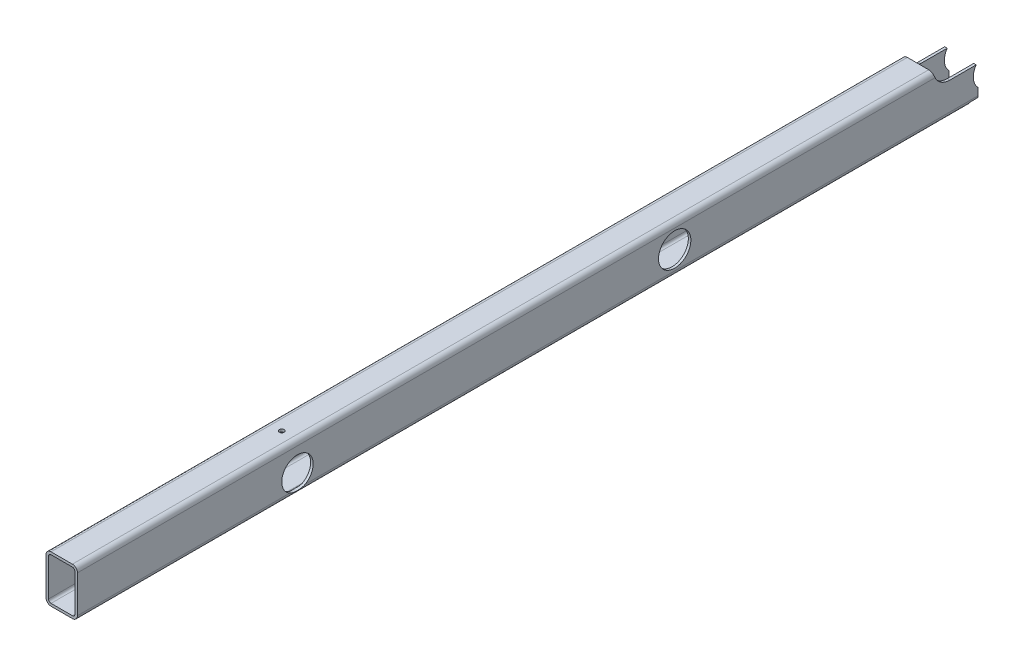
SolidWorks part; units mm, degrees
material "Q355"
ref_plane "前视基准面" through (0, 0, 0) normal (0, 0, 1) x (1, 0, 0)
ref_plane "上视基准面" through (0, 0, 0) normal (0, 1, 0) x (1, 0, 0)
ref_plane "右视基准面" through (0, 0, 0) normal (1, 0, 0) x (0, 0, -1)
sketch "草图1" plane through (0, 0, 0) normal (0, 0, 1) x (1, 0, 0)
  line L0 (16, -8) -> (84, -8)
  line L1 (16, 0) -> (84, 0)
  line L2 (0, -16) -> (0, -134)
  line L3 (16, -150) -> (84, -150)
  line L4 (100, -16) -> (100, -134)
  line L5 (92, -16) -> (92, -134)
  line L6 (16, -142) -> (84, -142)
  line L7 (8, -16) -> (8, -134)
  arc A0 (16, -150) -> (0, -134) centre (16, -134) cw
  arc A1 (84, -150) -> (100, -134) centre (84, -134) ccw
  arc A2 (100, -16) -> (84, 0) centre (84, -16) ccw
  arc A3 (0, -16) -> (16, 0) centre (16, -16) cw
  arc A4 (92, -16) -> (84, -8) centre (84, -16) ccw
  arc A5 (84, -142) -> (92, -134) centre (84, -134) ccw
  arc A6 (16, -142) -> (8, -134) centre (16, -134) cw
  arc A7 (8, -16) -> (16, -8) centre (16, -16) cw
  point P9 (100, -150)
  point P12 (100, 0)
  point P15 (0, 0)
  dimension "D3" = 16
  dimension "D1" = 150
  dimension "D2" = 100
  dimension "D4" = 8
extrude "凸台-拉伸1" add sketch "草图1" against normal blind 2865
sketch "草图2" plane through (0, 0, 0) normal (0, 1, 0) x (1, 0, 0)
  line L0 (100, 0) -> (30, 0)
  line L2 (30, 0) -> (30, 300)
  line L3 (30, 300) -> (100, 375)
  line L4 (100, 2865) -> (100, 0) construction
  line L5 (100, 375) -> (100, 0)
  line L6 (84, 0) -> (16, 0) construction
  dimension "D1" = 70
  dimension "D2" = 375
  dimension "D3" = 300
extrude "切除-拉伸1" [suppressed] cut sketch "草图2" against normal through all
sketch "草图4" plane through (100, 0, 0) normal (1, 0, 0) x (0, 0, -1)
  line L0 (2865, 0) -> (0, 0) construction
  line L1 (0, -16) -> (0, -134) construction
  circle A0 centre (2900, -75) radius 50
  dimension "D1" = 100
  dimension "D2" = 75
  dimension "D3" = 2900
extrude "切除-拉伸3" cut sketch "草图4" against normal through all
sketch "草图3" plane through (100, 0, 0) normal (1, 0, 0) x (0, 0, -1)
  line L0 (2775, -46) -> (2865, -46)
  line L1 (2865, 0) -> (0, 0) construction
  line L3 (2865, -134) -> (2865, -110.7071) construction
  line L4 (2865, -140) -> (2840, -140)
  line L5 (2865, 0) -> (2865, -46)
  line L6 (2840, -140) -> (2840, -150)
  line L7 (2865, -150) -> (0, -150) construction
  line L9 (2724.2457, 0) -> (2865, 0)
  line L10 (2865, -140) -> (2865, -150)
  line L11 (2865, -150) -> (2840, -150)
  line L13 (2900, -75) -> (2900, -154.9069) construction
  circle A1 centre (700, -90.5) radius 50
  arc A3 (2724.2457, 0) -> (2775, -46) centre (2775, 5) ccw
  circle A5 centre (1900, -75) radius 51.5
  circle A6 centre (2900, -75) radius 50 construction
  dimension "D1" = 25
  dimension "D2" = 102
  dimension "D3" = 90.5
  dimension "D6" = 2200
  dimension "D7" = 100
  dimension "D8" = 80
  dimension "D9" = 103
  dimension "D4" = 125
  dimension "D10" = 1000
  dimension "D5" = 10
extrude "切除-拉伸2" cut sketch "草图3" against normal through all
fillet "圆角2" radius 5 1 edges at (94.0619, -140, -2840)
fillet "圆角3" [suppressed] radius 8
sketch "草图5" plane through (0, 0, 0) normal (0, 1, 0) x (1, 0, 0)
  line L0 (0, 2728.5242) -> (0, 0) construction
  line L2 (0, 750) -> (0, 650) construction
  line L3 (0, 750) -> (0, 650) construction
  line L4 (0, 700) -> (103.3715, 700) construction
  circle A0 centre (50, 700) radius 7.5
  dimension "D1" = 15
  dimension "D2" = 50
extrude "切除-拉伸4" cut sketch "草图5" against normal up to next
ref_plane "基准面1" through (0, 0, -700) normal (0, 0, 1) x (1, 0, 0)
